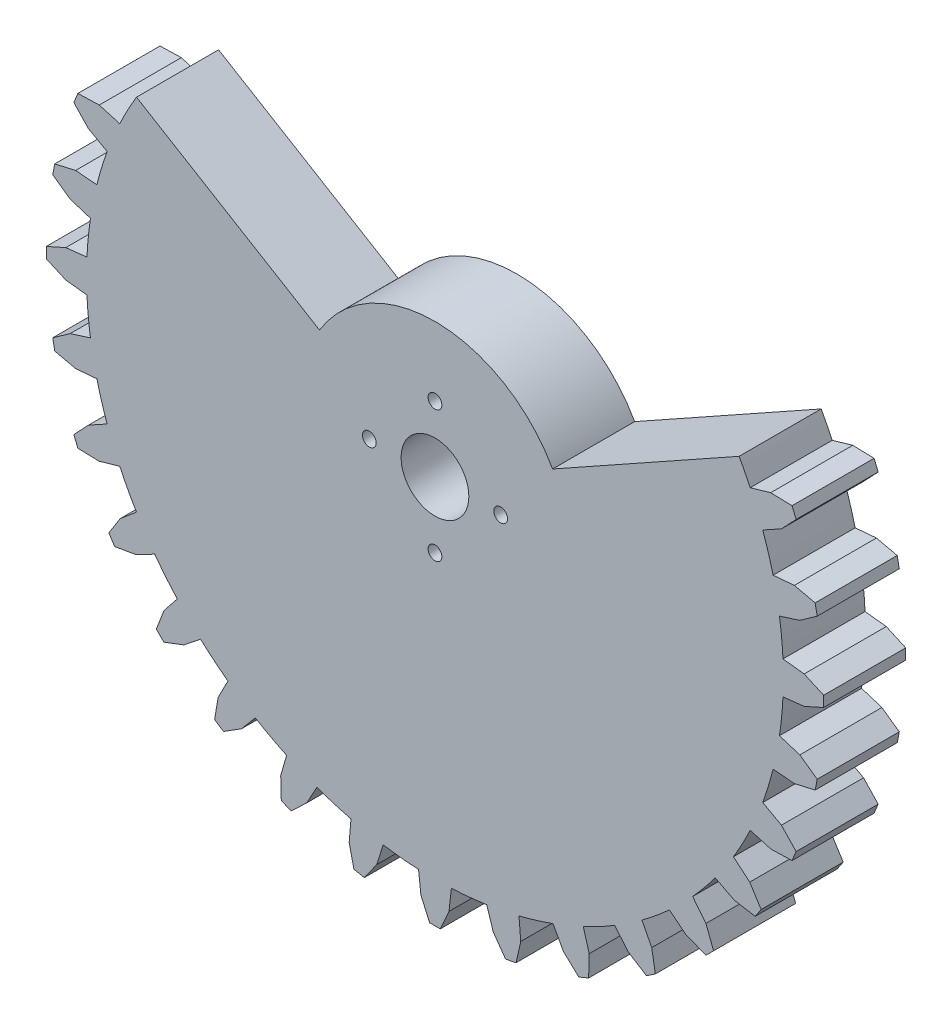
SolidWorks part; units mm, degrees
ref_plane "Plan de face" through (0, 0, 0) normal (0, 0, 1) x (1, 0, 0)
ref_plane "Plan de dessus" through (0, 0, 0) normal (0, 1, 0) x (1, 0, 0)
ref_plane "Plan de droite" through (0, 0, 0) normal (1, 0, 0) x (0, 0, -1)
sketch "Esquisse1" plane through (0, 0, 0) normal (0, 0, 1) x (1, 0, 0)
  line L0 (-2, 42.3979) -> (-1.7102, 44.9817)
  line L1 (0, 2.2889) -> (0, 19223.5431) construction
  line L2 (-1.7102, 44.9817) -> (-0.65, 47.3557)
  line L3 (-0.65, 47.3557) -> (0.65, 47.3557)
  line L4 (-2.3545, 0) -> (49997.6455, 0) construction
  line L5 (2, 42.3979) -> (1.7102, 44.9817)
  line L6 (1.7102, 44.9817) -> (0.65, 47.3557)
  line L7 (6.3098, 41.9734) -> (7.0982, 44.451)
  line L8 (7.0982, 44.451) -> (8.6011, 46.5726)
  line L9 (8.6011, 46.5726) -> (9.8761, 46.3189)
  line L10 (10.4528, 43.7837) -> (9.8761, 46.3189)
  line L11 (10.233, 41.193) -> (10.4528, 43.7837)
  line L12 (14.3772, 39.9359) -> (15.6337, 42.2121)
  line L13 (15.6337, 42.2121) -> (17.5217, 43.9997)
  line L14 (17.5217, 43.9997) -> (18.7228, 43.5022)
  line L15 (18.7937, 40.9032) -> (18.7228, 43.5022)
  line L16 (18.0727, 38.4051) -> (18.7937, 40.9032)
  line L17 (21.892, 36.3637) -> (23.5685, 38.351)
  line L18 (23.5685, 38.351) -> (25.769, 39.7359)
  line L19 (25.769, 39.7359) -> (26.8499, 39.0137)
  line L20 (26.4124, 36.4508) -> (26.8499, 39.0137)
  line L21 (25.2179, 34.1414) -> (26.4124, 36.4508)
  line L22 (28.5656, 31.394) -> (30.5975, 33.0161)
  line L23 (30.5975, 33.0161) -> (33.0259, 33.9451)
  line L24 (33.0259, 33.9451) -> (33.9451, 33.0259)
  line L25 (33.0161, 30.5975) -> (33.9451, 33.0259)
  line L26 (31.394, 28.5656) -> (33.0161, 30.5975)
  line L27 (34.1414, 25.2179) -> (36.4508, 26.4124)
  line L28 (36.4508, 26.4124) -> (39.0137, 26.8499)
  line L29 (39.0137, 26.8499) -> (39.7359, 25.769)
  line L30 (38.351, 23.5685) -> (39.7359, 25.769)
  line L31 (36.3637, 21.892) -> (38.351, 23.5685)
  line L32 (38.4051, 18.0727) -> (40.9032, 18.7937)
  line L33 (40.9032, 18.7937) -> (43.5022, 18.7228)
  line L34 (43.5022, 18.7228) -> (43.9997, 17.5217)
  line L35 (42.2121, 15.6337) -> (43.9997, 17.5217)
  line L36 (39.9359, 14.3772) -> (42.2121, 15.6337)
  line L37 (41.193, 10.233) -> (43.7837, 10.4528)
  line L38 (43.7837, 10.4528) -> (46.3189, 9.8761)
  line L39 (46.3189, 9.8761) -> (46.5726, 8.6011)
  line L40 (44.451, 7.0982) -> (46.5726, 8.6011)
  line L41 (41.9734, 6.3098) -> (44.451, 7.0982)
  line L42 (42.3979, 2) -> (44.9817, 1.7102)
  line L43 (44.9817, 1.7102) -> (47.3557, 0.65)
  line L44 (47.3557, 0.65) -> (47.3557, -0.65)
  line L45 (44.9817, -1.7102) -> (47.3557, -0.65)
  line L46 (42.3979, -2) -> (44.9817, -1.7102)
  line L47 (41.9734, -6.3098) -> (44.451, -7.0982)
  line L48 (44.451, -7.0982) -> (46.5726, -8.6011)
  line L49 (46.5726, -8.6011) -> (46.3189, -9.8761)
  line L50 (43.7837, -10.4528) -> (46.3189, -9.8761)
  line L51 (41.193, -10.233) -> (43.7837, -10.4528)
  line L52 (39.9359, -14.3772) -> (42.2121, -15.6337)
  line L53 (42.2121, -15.6337) -> (43.9997, -17.5217)
  line L54 (43.9997, -17.5217) -> (43.5022, -18.7228)
  line L55 (40.9032, -18.7937) -> (43.5022, -18.7228)
  line L56 (38.4051, -18.0727) -> (40.9032, -18.7937)
  line L57 (36.3637, -21.892) -> (38.351, -23.5685)
  line L58 (38.351, -23.5685) -> (39.7359, -25.769)
  line L59 (39.7359, -25.769) -> (39.0137, -26.8499)
  line L60 (36.4508, -26.4124) -> (39.0137, -26.8499)
  line L61 (34.1414, -25.2179) -> (36.4508, -26.4124)
  line L62 (31.394, -28.5656) -> (33.0161, -30.5975)
  line L63 (33.0161, -30.5975) -> (33.9451, -33.0259)
  line L64 (33.9451, -33.0259) -> (33.0259, -33.9451)
  line L65 (30.5975, -33.0161) -> (33.0259, -33.9451)
  line L66 (28.5656, -31.394) -> (30.5975, -33.0161)
  line L67 (25.2179, -34.1414) -> (26.4124, -36.4508)
  line L68 (26.4124, -36.4508) -> (26.8499, -39.0137)
  line L69 (26.8499, -39.0137) -> (25.769, -39.7359)
  line L70 (23.5685, -38.351) -> (25.769, -39.7359)
  line L71 (21.892, -36.3637) -> (23.5685, -38.351)
  line L72 (18.0727, -38.4051) -> (18.7937, -40.9032)
  line L73 (18.7937, -40.9032) -> (18.7228, -43.5022)
  line L74 (18.7228, -43.5022) -> (17.5217, -43.9997)
  line L75 (15.6337, -42.2121) -> (17.5217, -43.9997)
  line L76 (14.3772, -39.9359) -> (15.6337, -42.2121)
  line L77 (10.233, -41.193) -> (10.4528, -43.7837)
  line L78 (10.4528, -43.7837) -> (9.8761, -46.3189)
  line L79 (9.8761, -46.3189) -> (8.6011, -46.5726)
  line L80 (7.0982, -44.451) -> (8.6011, -46.5726)
  line L81 (6.3098, -41.9734) -> (7.0982, -44.451)
  line L82 (2, -42.3979) -> (1.7102, -44.9817)
  line L83 (1.7102, -44.9817) -> (0.65, -47.3557)
  line L84 (0.65, -47.3557) -> (-0.65, -47.3557)
  line L85 (-1.7102, -44.9817) -> (-0.65, -47.3557)
  line L86 (-2, -42.3979) -> (-1.7102, -44.9817)
  line L87 (-6.3098, -41.9734) -> (-7.0982, -44.451)
  line L88 (-7.0982, -44.451) -> (-8.6011, -46.5726)
  line L89 (-8.6011, -46.5726) -> (-9.8761, -46.3189)
  line L90 (-10.4528, -43.7837) -> (-9.8761, -46.3189)
  line L91 (-10.233, -41.193) -> (-10.4528, -43.7837)
  line L92 (-14.3772, -39.9359) -> (-15.6337, -42.2121)
  line L93 (-15.6337, -42.2121) -> (-17.5217, -43.9997)
  line L94 (-17.5217, -43.9997) -> (-18.7228, -43.5022)
  line L95 (-18.7937, -40.9032) -> (-18.7228, -43.5022)
  line L96 (-18.0727, -38.4051) -> (-18.7937, -40.9032)
  line L97 (-21.892, -36.3637) -> (-23.5685, -38.351)
  line L98 (-23.5685, -38.351) -> (-25.769, -39.7359)
  line L99 (-25.769, -39.7359) -> (-26.8499, -39.0137)
  line L100 (-26.4124, -36.4508) -> (-26.8499, -39.0137)
  line L101 (-25.2179, -34.1414) -> (-26.4124, -36.4508)
  line L102 (-28.5656, -31.394) -> (-30.5975, -33.0161)
  line L103 (-30.5975, -33.0161) -> (-33.0259, -33.9451)
  line L104 (-33.0259, -33.9451) -> (-33.9451, -33.0259)
  line L105 (-33.0161, -30.5975) -> (-33.9451, -33.0259)
  line L106 (-31.394, -28.5656) -> (-33.0161, -30.5975)
  line L107 (-34.1414, -25.2179) -> (-36.4508, -26.4124)
  line L108 (-36.4508, -26.4124) -> (-39.0137, -26.8499)
  line L109 (-39.0137, -26.8499) -> (-39.7359, -25.769)
  line L110 (-38.351, -23.5685) -> (-39.7359, -25.769)
  line L111 (-36.3637, -21.892) -> (-38.351, -23.5685)
  line L112 (-38.4051, -18.0727) -> (-40.9032, -18.7937)
  line L113 (-40.9032, -18.7937) -> (-43.5022, -18.7228)
  line L114 (-43.5022, -18.7228) -> (-43.9997, -17.5217)
  line L115 (-42.2121, -15.6337) -> (-43.9997, -17.5217)
  line L116 (-39.9359, -14.3772) -> (-42.2121, -15.6337)
  line L117 (-41.193, -10.233) -> (-43.7837, -10.4528)
  line L118 (-43.7837, -10.4528) -> (-46.3189, -9.8761)
  line L119 (-46.3189, -9.8761) -> (-46.5726, -8.6011)
  line L120 (-44.451, -7.0982) -> (-46.5726, -8.6011)
  line L121 (-41.9734, -6.3098) -> (-44.451, -7.0982)
  line L122 (-42.3979, -2) -> (-44.9817, -1.7102)
  line L123 (-44.9817, -1.7102) -> (-47.3557, -0.65)
  line L124 (-47.3557, -0.65) -> (-47.3557, 0.65)
  line L125 (-44.9817, 1.7102) -> (-47.3557, 0.65)
  line L126 (-42.3979, 2) -> (-44.9817, 1.7102)
  line L127 (-41.9734, 6.3098) -> (-44.451, 7.0982)
  line L128 (-44.451, 7.0982) -> (-46.5726, 8.6011)
  line L129 (-46.5726, 8.6011) -> (-46.3189, 9.8761)
  line L130 (-43.7837, 10.4528) -> (-46.3189, 9.8761)
  line L131 (-41.193, 10.233) -> (-43.7837, 10.4528)
  line L132 (-39.9359, 14.3772) -> (-42.2121, 15.6337)
  line L133 (-42.2121, 15.6337) -> (-43.9997, 17.5217)
  line L134 (-43.9997, 17.5217) -> (-43.5022, 18.7228)
  line L135 (-40.9032, 18.7937) -> (-43.5022, 18.7228)
  line L136 (-38.4051, 18.0727) -> (-40.9032, 18.7937)
  line L137 (-36.3637, 21.892) -> (-38.351, 23.5685)
  line L138 (-38.351, 23.5685) -> (-39.7359, 25.769)
  line L139 (-39.7359, 25.769) -> (-39.0137, 26.8499)
  line L140 (-36.4508, 26.4124) -> (-39.0137, 26.8499)
  line L141 (-34.1414, 25.2179) -> (-36.4508, 26.4124)
  line L142 (-31.394, 28.5656) -> (-33.0161, 30.5975)
  line L143 (-33.0161, 30.5975) -> (-33.9451, 33.0259)
  line L144 (-33.9451, 33.0259) -> (-33.0259, 33.9451)
  line L145 (-30.5975, 33.0161) -> (-33.0259, 33.9451)
  line L146 (-28.5656, 31.394) -> (-30.5975, 33.0161)
  line L147 (-25.2179, 34.1414) -> (-26.4124, 36.4508)
  line L148 (-26.4124, 36.4508) -> (-26.8499, 39.0137)
  line L149 (-26.8499, 39.0137) -> (-25.769, 39.7359)
  line L150 (-23.5685, 38.351) -> (-25.769, 39.7359)
  line L151 (-21.892, 36.3637) -> (-23.5685, 38.351)
  line L152 (-18.0727, 38.4051) -> (-18.7937, 40.9032)
  line L153 (-18.7937, 40.9032) -> (-18.7228, 43.5022)
  line L154 (-18.7228, 43.5022) -> (-17.5217, 43.9997)
  line L155 (-15.6337, 42.2121) -> (-17.5217, 43.9997)
  line L156 (-14.3772, 39.9359) -> (-15.6337, 42.2121)
  line L157 (-10.233, 41.193) -> (-10.4528, 43.7837)
  line L158 (-10.4528, 43.7837) -> (-9.8761, 46.3189)
  line L159 (-9.8761, 46.3189) -> (-8.6011, 46.5726)
  line L160 (-7.0982, 44.451) -> (-8.6011, 46.5726)
  line L161 (-6.3098, 41.9734) -> (-7.0982, 44.451)
  arc A17 (6.3098, 41.9734) -> (2, 42.3979) centre (0, 0) ccw
  arc A18 (14.3772, 39.9359) -> (10.233, 41.193) centre (0, 0) ccw
  arc A19 (21.892, 36.3637) -> (18.0727, 38.4051) centre (0, 0) ccw
  arc A20 (28.5656, 31.394) -> (25.2179, 34.1414) centre (0, 0) ccw
  arc A21 (34.1414, 25.2179) -> (31.394, 28.5656) centre (0, 0) ccw
  arc A22 (38.4051, 18.0727) -> (36.3637, 21.892) centre (0, 0) ccw
  arc A23 (41.193, 10.233) -> (39.9359, 14.3772) centre (0, 0) ccw
  arc A24 (42.3979, 2) -> (41.9734, 6.3098) centre (0, 0) ccw
  arc A25 (41.9734, -6.3098) -> (42.3979, -2) centre (0, 0) ccw
  arc A26 (39.9359, -14.3772) -> (41.193, -10.233) centre (0, 0) ccw
  arc A27 (36.3637, -21.892) -> (38.4051, -18.0727) centre (0, 0) ccw
  arc A28 (31.394, -28.5656) -> (34.1414, -25.2179) centre (0, 0) ccw
  arc A29 (25.2179, -34.1414) -> (28.5656, -31.394) centre (0, 0) ccw
  arc A30 (18.0727, -38.4051) -> (21.892, -36.3637) centre (0, 0) ccw
  arc A31 (10.233, -41.193) -> (14.3772, -39.9359) centre (0, 0) ccw
  arc A32 (2, -42.3979) -> (6.3098, -41.9734) centre (0, 0) ccw
  arc A33 (-6.3098, -41.9734) -> (-2, -42.3979) centre (0, 0) ccw
  arc A34 (-14.3772, -39.9359) -> (-10.233, -41.193) centre (0, 0) ccw
  arc A35 (-21.892, -36.3637) -> (-18.0727, -38.4051) centre (0, 0) ccw
  arc A36 (-28.5656, -31.394) -> (-25.2179, -34.1414) centre (0, 0) ccw
  arc A37 (-34.1414, -25.2179) -> (-31.394, -28.5656) centre (0, 0) ccw
  arc A38 (-38.4051, -18.0727) -> (-36.3637, -21.892) centre (0, 0) ccw
  arc A39 (-42.3979, -2) -> (-41.9734, -6.3098) centre (0, 0) ccw
  arc A40 (-41.9734, 6.3098) -> (-42.3979, 2) centre (0, 0) ccw
  arc A41 (-39.9359, 14.3772) -> (-41.193, 10.233) centre (0, 0) ccw
  arc A42 (-36.3637, 21.892) -> (-38.4051, 18.0727) centre (0, 0) ccw
  arc A43 (-31.394, 28.5656) -> (-34.1414, 25.2179) centre (0, 0) ccw
  arc A44 (-25.2179, 34.1414) -> (-28.5656, 31.394) centre (0, 0) ccw
  arc A45 (-18.0727, 38.4051) -> (-21.892, 36.3637) centre (0, 0) ccw
  arc A46 (-10.233, 41.193) -> (-14.3772, 39.9359) centre (0, 0) ccw
  arc A47 (-2, 42.3979) -> (-6.3098, 41.9734) centre (0, 0) ccw
  arc A48 (-41.193, -10.233) -> (-39.9359, -14.3772) centre (0, 0) ccw
  point P17 (0, 47.3557)
  point P83 (0, 0)
  point P204 (0, 0)
  dimension "D1" = 84.89
  dimension "D2" = 32
  dimension "D3" = 2.6
  dimension "D4" = 83.6
  dimension "D5" = 2
  dimension "D6" = 2.6
  dimension "D7" = 0.65
extrude "Boss.-Extru.1" add sketch "Esquisse1" along normal blind 10
sketch "Esquisse2" plane through (0, 0, 10) normal (0, 0, 1) x (1, 0, 0)
  circle A3 centre (0, 0) radius 8 construction
  circle A4 centre (0, 8) radius 0.8387
  circle A5 centre (0, 0) radius 4.125
  circle A6 centre (8, 0) radius 0.8387
  circle A7 centre (0, -8) radius 0.8387
  circle A8 centre (-8, 0) radius 0.8387
  point P16 (0, 0)
  dimension "D1" = 16
  dimension "D2" = 1.6774
  dimension "D3" = 8.25
  dimension "D4" = 4
extrude "Enlèv. mat.-Extru.3" cut sketch "Esquisse2" against normal up to surface (10 mm away) up to face at (0, 0, 0)
sketch "Esquisse3" plane through (0, 0, 10) normal (0, 0, 1) x (1, 0, 0)
  line L0 (37.0515, 20.7066) -> (0, 0) construction
  line L1 (0, 0) -> (-36.3637, 21.892) construction
  line L2 (-36.3637, 21.892) -> (-14.0654, 8.4678)
  line L3 (37.0515, 20.7066) -> (14.3315, 8.0093)
  line L4 (-36.3637, 21.892) -> (-44.7714, 26.9538)
  line L5 (37.0515, 20.7066) -> (45.6183, 25.4942)
  arc A0 (37.0515, 20.7066) -> (-36.3637, 21.892) centre (0, 0) ccw construction
  arc A1 (-2, 42.3979) -> (-6.3098, 41.9734) centre (0, 0) ccw construction
  arc A2 (-14.0654, 8.4678) -> (14.3315, 8.0093) centre (0, 0) cw
  circle A3 centre (0, 0) radius 4.125 construction
  arc A4 (-44.7714, 26.9538) -> (45.6183, 25.4942) centre (0.1388, 8.5967) cw
  dimension "D1" = 119.752
extrude "Enlèv. mat.-Extru.6" cut sketch "Esquisse3" against normal up to surface (10 mm away) up to face at (0.8387, 8, 0)
equation "\"L\"= 20cm'Longueur de tensionnement"
